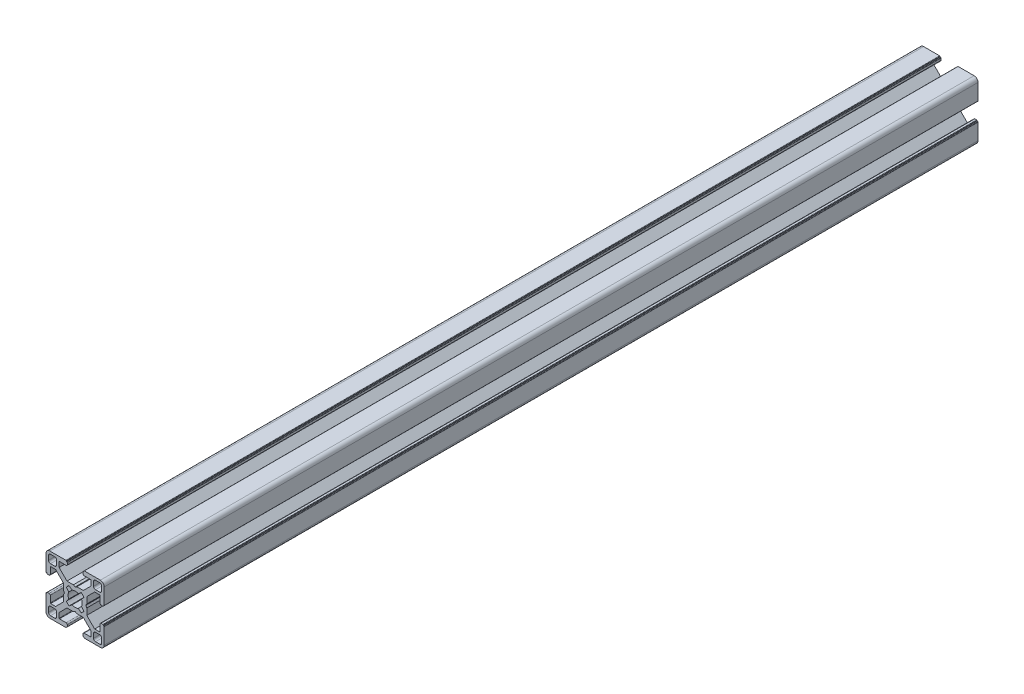
SolidWorks part; units mm, degrees
material "6063 Aluminum Alloy"
ref_plane "Płaszczyzna przednia" through (0, 0, 0) normal (0, 0, 1) x (1, 0, 0)
ref_plane "Płaszczyzna górna" through (0, 0, 0) normal (0, 1, 0) x (1, 0, 0)
ref_plane "Płaszczyzna prawa" through (0, 0, 0) normal (1, 0, 0) x (0, 0, -1)
sketch "Szkic1" plane through (0, 0, 0) normal (0, 0, 1) x (1, 0, 0)
  line L0 (12.7, 13.7) -> (10.5, 13.7)
  line L1 (9.5, 12.7) -> (9.5, 10.5)
  line L2 (10.5, 9.5) -> (12.7, 9.5)
  line L3 (13.7, 10.5) -> (13.7, 12.7)
  line L4 (-1.5829, 3.2889) -> (-3.1172, 4.5314)
  line L5 (-4.5314, 3.1172) -> (-3.2889, 1.5829)
  line L6 (-3.2889, -1.5829) -> (-4.5314, -3.1172)
  line L7 (-3.1172, -4.5314) -> (-1.5829, -3.2889)
  line L8 (1.5829, -3.2889) -> (3.1172, -4.5314)
  line L9 (4.5314, -3.1172) -> (3.2889, -1.5829)
  line L10 (3.2889, 1.5829) -> (4.5314, 3.1172)
  line L11 (3.1172, 4.5314) -> (1.5829, 3.2889)
  line L12 (-12.7, -13.7) -> (-10.5, -13.7)
  line L13 (-9.5, -12.7) -> (-9.5, -10.5)
  line L14 (-10.5, -9.5) -> (-12.7, -9.5)
  line L15 (-13.7, -10.5) -> (-13.7, -12.7)
  line L16 (13.7, -12.7) -> (13.7, -10.5)
  line L17 (12.7, -9.5) -> (10.5, -9.5)
  line L18 (9.5, -10.5) -> (9.5, -12.7)
  line L19 (-10.5, 13.7) -> (-12.7, 13.7)
  line L20 (-13.7, 12.7) -> (-13.7, 10.5)
  line L21 (-12.7, 9.5) -> (-10.5, 9.5)
  line L22 (-9.5, 10.5) -> (-9.5, 12.7)
  line L23 (10.5, -13.7) -> (12.7, -13.7)
  line L24 (0, -5.48) -> (0.9007, -6)
  line L25 (0.9007, -6) -> (4.2039, -6)
  line L26 (4.2039, -6) -> (8.25, -10.0461)
  line L27 (8.25, -10.0461) -> (8.25, -12.6)
  line L28 (8.05, -12.8) -> (4.65, -12.8)
  line L29 (4.05, -13.4) -> (4.05, -14.3)
  line L30 (4.25, -14.5) -> (4.35, -14.5)
  line L31 (4.55, -14.7) -> (4.55, -14.8)
  line L32 (4.75, -15) -> (13, -15)
  line L33 (15, -13) -> (15, -4.75)
  line L34 (14.8, -4.55) -> (14.7, -4.55)
  line L35 (14.5, -4.35) -> (14.5, -4.25)
  line L36 (14.3, -4.05) -> (13.4, -4.05)
  line L37 (12.8, -4.65) -> (12.8, -8.05)
  line L38 (12.6, -8.25) -> (10.0461, -8.25)
  line L39 (10.0461, -8.25) -> (6, -4.2039)
  line L40 (6, -4.2039) -> (6, -0.9007)
  line L41 (6, -0.9007) -> (5.48, 0)
  line L42 (5.48, 0) -> (6, 0.9007)
  line L43 (6, 0.9007) -> (6, 4.2039)
  line L44 (6, 4.2039) -> (10.0461, 8.25)
  line L45 (10.0461, 8.25) -> (12.6, 8.25)
  line L46 (12.8, 8.05) -> (12.8, 4.65)
  line L47 (13.4, 4.05) -> (14.3, 4.05)
  line L48 (14.5, 4.25) -> (14.5, 4.35)
  line L49 (14.7, 4.55) -> (14.8, 4.55)
  line L50 (15, 4.75) -> (15, 13)
  line L51 (13, 15) -> (4.75, 15)
  line L52 (4.55, 14.8) -> (4.55, 14.7)
  line L53 (4.35, 14.5) -> (4.25, 14.5)
  line L54 (4.05, 14.3) -> (4.05, 13.4)
  line L55 (4.65, 12.8) -> (8.05, 12.8)
  line L56 (8.25, 12.6) -> (8.25, 10.0461)
  line L57 (8.25, 10.0461) -> (4.2039, 6)
  line L58 (4.2039, 6) -> (0.9007, 6)
  line L59 (0.9007, 6) -> (0, 5.48)
  line L60 (0, 5.48) -> (-0.9007, 6)
  line L61 (-0.9007, 6) -> (-4.2039, 6)
  line L62 (-4.2039, 6) -> (-8.25, 10.0461)
  line L63 (-8.25, 10.0461) -> (-8.25, 12.6)
  line L64 (-8.05, 12.8) -> (-4.65, 12.8)
  line L65 (-4.05, 13.4) -> (-4.05, 14.3)
  line L66 (-4.25, 14.5) -> (-4.35, 14.5)
  line L67 (-4.55, 14.7) -> (-4.55, 14.8)
  line L68 (-4.75, 15) -> (-13, 15)
  line L69 (-15, 13) -> (-15, 4.75)
  line L70 (-14.8, 4.55) -> (-14.7, 4.55)
  line L71 (-14.5, 4.35) -> (-14.5, 4.25)
  line L72 (-14.3, 4.05) -> (-13.4, 4.05)
  line L73 (-12.8, 4.65) -> (-12.8, 8.05)
  line L74 (-12.6, 8.25) -> (-10.0461, 8.25)
  line L75 (-10.0461, 8.25) -> (-6, 4.2039)
  line L76 (-6, 4.2039) -> (-6, 0.9007)
  line L77 (-6, 0.9007) -> (-5.48, 0)
  line L78 (-5.48, 0) -> (-6, -0.9007)
  line L79 (-6, -0.9007) -> (-6, -4.2039)
  line L80 (-6, -4.2039) -> (-10.0461, -8.25)
  line L81 (-10.0461, -8.25) -> (-12.6, -8.25)
  line L82 (-12.8, -8.05) -> (-12.8, -4.65)
  line L83 (-13.4, -4.05) -> (-14.3, -4.05)
  line L84 (-14.5, -4.25) -> (-14.5, -4.35)
  line L85 (-14.7, -4.55) -> (-14.8, -4.55)
  line L86 (-15, -4.75) -> (-15, -13)
  line L87 (-13, -15) -> (-4.75, -15)
  line L88 (-4.55, -14.8) -> (-4.55, -14.7)
  line L89 (-4.35, -14.5) -> (-4.25, -14.5)
  line L90 (-4.05, -14.3) -> (-4.05, -13.4)
  line L91 (-4.65, -12.8) -> (-8.05, -12.8)
  line L92 (-8.25, -12.6) -> (-8.25, -10.0461)
  line L93 (-8.25, -10.0461) -> (-4.2039, -6)
  line L94 (-4.2039, -6) -> (-0.9007, -6)
  line L95 (-0.9007, -6) -> (0, -5.48)
  line L96 (-3.8891, -3.8891) -> (3.8891, 3.8891) construction
  line L97 (-3.8891, 3.8891) -> (3.8891, -3.8891) construction
  line L98 (55, 0) -> (-55, 0) construction
  arc A0 (10.5, 13.7) -> (9.5, 12.7) centre (10.5, 12.7) ccw
  arc A1 (9.5, 10.5) -> (10.5, 9.5) centre (10.5, 10.5) ccw
  arc A2 (12.7, 9.5) -> (13.7, 10.5) centre (12.7, 10.5) ccw
  arc A3 (13.7, 12.7) -> (12.7, 13.7) centre (12.7, 12.7) ccw
  arc A4 (-3.1172, 4.5314) -> (-4.5314, 3.1172) centre (0, 0) ccw
  arc A5 (-3.2889, 1.5829) -> (-3.2889, -1.5829) centre (0, 0) ccw
  arc A6 (-4.5314, -3.1172) -> (-3.1172, -4.5314) centre (0, 0) ccw
  arc A7 (-1.5829, -3.2889) -> (1.5829, -3.2889) centre (0, 0) ccw
  arc A8 (3.1172, -4.5314) -> (4.5314, -3.1172) centre (0, 0) ccw
  arc A9 (3.2889, -1.5829) -> (3.2889, 1.5829) centre (0, 0) ccw
  arc A10 (4.5314, 3.1172) -> (3.1172, 4.5314) centre (0, 0) ccw
  arc A11 (1.5829, 3.2889) -> (-1.5829, 3.2889) centre (0, 0) ccw
  arc A12 (-10.5, -13.7) -> (-9.5, -12.7) centre (-10.5, -12.7) ccw
  arc A13 (-9.5, -10.5) -> (-10.5, -9.5) centre (-10.5, -10.5) ccw
  arc A14 (-12.7, -9.5) -> (-13.7, -10.5) centre (-12.7, -10.5) ccw
  arc A15 (-13.7, -12.7) -> (-12.7, -13.7) centre (-12.7, -12.7) ccw
  arc A16 (12.7, -13.7) -> (13.7, -12.7) centre (12.7, -12.7) ccw
  arc A17 (13.7, -10.5) -> (12.7, -9.5) centre (12.7, -10.5) ccw
  arc A18 (10.5, -9.5) -> (9.5, -10.5) centre (10.5, -10.5) ccw
  arc A19 (9.5, -12.7) -> (10.5, -13.7) centre (10.5, -12.7) ccw
  arc A20 (-12.7, 13.7) -> (-13.7, 12.7) centre (-12.7, 12.7) ccw
  arc A21 (-13.7, 10.5) -> (-12.7, 9.5) centre (-12.7, 10.5) ccw
  arc A22 (-10.5, 9.5) -> (-9.5, 10.5) centre (-10.5, 10.5) ccw
  arc A23 (-9.5, 12.7) -> (-10.5, 13.7) centre (-10.5, 12.7) ccw
  arc A24 (8.05, -12.8) -> (8.25, -12.6) centre (8.05, -12.6) ccw
  arc A25 (4.65, -12.8) -> (4.05, -13.4) centre (4.65, -13.4) ccw
  arc A26 (4.05, -14.3) -> (4.25, -14.5) centre (4.25, -14.3) ccw
  arc A27 (4.55, -14.7) -> (4.35, -14.5) centre (4.35, -14.7) ccw
  arc A28 (4.55, -14.8) -> (4.75, -15) centre (4.75, -14.8) ccw
  arc A29 (13, -15) -> (15, -13) centre (13, -13) ccw
  arc A30 (15, -4.75) -> (14.8, -4.55) centre (14.8, -4.75) ccw
  arc A31 (14.5, -4.35) -> (14.7, -4.55) centre (14.7, -4.35) ccw
  arc A32 (14.5, -4.25) -> (14.3, -4.05) centre (14.3, -4.25) ccw
  arc A33 (13.4, -4.05) -> (12.8, -4.65) centre (13.4, -4.65) ccw
  arc A34 (12.6, -8.25) -> (12.8, -8.05) centre (12.6, -8.05) ccw
  arc A35 (12.8, 8.05) -> (12.6, 8.25) centre (12.6, 8.05) ccw
  arc A36 (12.8, 4.65) -> (13.4, 4.05) centre (13.4, 4.65) ccw
  arc A37 (14.3, 4.05) -> (14.5, 4.25) centre (14.3, 4.25) ccw
  arc A38 (14.7, 4.55) -> (14.5, 4.35) centre (14.7, 4.35) ccw
  arc A39 (14.8, 4.55) -> (15, 4.75) centre (14.8, 4.75) ccw
  arc A40 (15, 13) -> (13, 15) centre (13, 13) ccw
  arc A41 (4.75, 15) -> (4.55, 14.8) centre (4.75, 14.8) ccw
  arc A42 (4.35, 14.5) -> (4.55, 14.7) centre (4.35, 14.7) ccw
  arc A43 (4.25, 14.5) -> (4.05, 14.3) centre (4.25, 14.3) ccw
  arc A44 (4.05, 13.4) -> (4.65, 12.8) centre (4.65, 13.4) ccw
  arc A45 (8.25, 12.6) -> (8.05, 12.8) centre (8.05, 12.6) ccw
  arc A46 (-8.05, 12.8) -> (-8.25, 12.6) centre (-8.05, 12.6) ccw
  arc A47 (-4.65, 12.8) -> (-4.05, 13.4) centre (-4.65, 13.4) ccw
  arc A48 (-4.05, 14.3) -> (-4.25, 14.5) centre (-4.25, 14.3) ccw
  arc A49 (-4.55, 14.7) -> (-4.35, 14.5) centre (-4.35, 14.7) ccw
  arc A50 (-4.55, 14.8) -> (-4.75, 15) centre (-4.75, 14.8) ccw
  arc A51 (-13, 15) -> (-15, 13) centre (-13, 13) ccw
  arc A52 (-15, 4.75) -> (-14.8, 4.55) centre (-14.8, 4.75) ccw
  arc A53 (-14.5, 4.35) -> (-14.7, 4.55) centre (-14.7, 4.35) ccw
  arc A54 (-14.5, 4.25) -> (-14.3, 4.05) centre (-14.3, 4.25) ccw
  arc A55 (-13.4, 4.05) -> (-12.8, 4.65) centre (-13.4, 4.65) ccw
  arc A56 (-12.6, 8.25) -> (-12.8, 8.05) centre (-12.6, 8.05) ccw
  arc A57 (-12.8, -8.05) -> (-12.6, -8.25) centre (-12.6, -8.05) ccw
  arc A58 (-12.8, -4.65) -> (-13.4, -4.05) centre (-13.4, -4.65) ccw
  arc A59 (-14.3, -4.05) -> (-14.5, -4.25) centre (-14.3, -4.25) ccw
  arc A60 (-14.7, -4.55) -> (-14.5, -4.35) centre (-14.7, -4.35) ccw
  arc A61 (-14.8, -4.55) -> (-15, -4.75) centre (-14.8, -4.75) ccw
  arc A62 (-15, -13) -> (-13, -15) centre (-13, -13) ccw
  arc A63 (-4.75, -15) -> (-4.55, -14.8) centre (-4.75, -14.8) ccw
  arc A64 (-4.35, -14.5) -> (-4.55, -14.7) centre (-4.35, -14.7) ccw
  arc A65 (-4.25, -14.5) -> (-4.05, -14.3) centre (-4.25, -14.3) ccw
  arc A66 (-4.05, -13.4) -> (-4.65, -12.8) centre (-4.65, -13.4) ccw
  arc A67 (-8.25, -12.6) -> (-8.05, -12.8) centre (-8.05, -12.6) ccw
  dimension "D1" = 3.65
  dimension "D7" = 2
  dimension "D9" = 3.65
  dimension "D10" = 5.5
  dimension "D23" = 1
  dimension "D37" = 0.2
  dimension "D59" = 0.6
  dimension "D60" = 0.2
  dimension "D63" = 0.2
  dimension "D64" = 0.2
  dimension "D67" = 0.2
  dimension "D68" = 0.2
  dimension "D69" = 0.2
  dimension "D73" = 0.2
  dimension "D75" = 0.2
  dimension "D76" = 0.2
  dimension "D2" = 30
  dimension "D3" = 30
  dimension "D4" = 8.1
  dimension "D5" = 15
  dimension "D6" = 15
  dimension "D8" = 4.05
  dimension "D11" = 45
  dimension "D12" = 6
  dimension "D13" = 2
  dimension "D14" = 12
  dimension "D15" = 6
  dimension "D16" = 12
  dimension "D17" = 6
  dimension "D18" = 12
  dimension "D19" = 6
  dimension "D20" = 12
  dimension "D21" = 1.3
  dimension "D22" = 1.3
  dimension "D24" = 1.3
  dimension "D25" = 4.2
  dimension "D26" = 4.2
  dimension "D27" = 4.2
  dimension "D28" = 1.3
  dimension "D29" = 4.2
  dimension "D30" = 16.5
  dimension "D31" = 8.25
  dimension "D32" = 2.54
  dimension "D33" = 1.27
  dimension "D34" = 2.54
  dimension "D35" = 1.27
  dimension "D36" = 2.2
  dimension "D38" = 2.2
  dimension "D39" = 2.2
  dimension "D40" = 6
  dimension "D41" = 6
  dimension "D42" = 12
  dimension "D43" = 2
  dimension "D44" = 2
  dimension "D45" = 2
  dimension "D46" = 2.2
  dimension "D47" = 16.5
  dimension "D48" = 8.25
  dimension "D49" = 6
  dimension "D50" = 8.1
  dimension "D51" = 4.05
  dimension "D52" = 0.52
  dimension "D53" = 120
  dimension "D54" = 60
  dimension "D55" = 0.52
  dimension "D56" = 0.52
  dimension "D57" = 0.52
  dimension "D58" = 120
  dimension "D61" = 0.5
  dimension "D62" = 0.5
  dimension "D65" = 0.5
  dimension "D66" = 0.5
  dimension "D70" = 0.5
  dimension "D71" = 0.5
  dimension "D72" = 0.5
  dimension "D74" = 0.5
extrude "Dodanie-wyciągnięcie1" add sketch "Szkic1" along normal mid plane 450
equation "\"D5@Szkic1\"=\"D2@Szkic1\"/2"
equation "\"D6@Szkic1\"=\"D3@Szkic1\"/2"
equation "\"D8@Szkic1\"=\"D4@Szkic1\"/2"
equation "\"D14@Szkic1\"=\"D12@Szkic1\"*2"
equation "\"D15@Szkic1\"=\"D12@Szkic1\""
equation "\"D17@Szkic1\"=\"D12@Szkic1\""
equation "\"D19@Szkic1\"=\"D12@Szkic1\""
equation "\"D31@Szkic1\"=\"D30@Szkic1\"/2"
equation "\"D33@Szkic1\"=\"D32@Szkic1\"/2"
equation "\"D35@Szkic1\"=\"D34@Szkic1\"/2"
equation "\"D42@Szkic1\"=\"D40@Szkic1\"*2"
equation "\"D46@Szkic1\"=\"D36@Szkic1\""
equation "\"D47@Szkic1\"=\"D30@Szkic1\""
equation "\"D48@Szkic1\"=\"D31@Szkic1\""
equation "\"D51@Szkic1\"=\"D50@Szkic1\"/2"
equation "\"D54@Szkic1\"=\"D53@Szkic1\"/2"
equation "\"D55@Szkic1\"=\"D52@Szkic1\""
equation "\"D56@Szkic1\"=\"D52@Szkic1\""
equation "\"D57@Szkic1\"=\"D52@Szkic1\""
